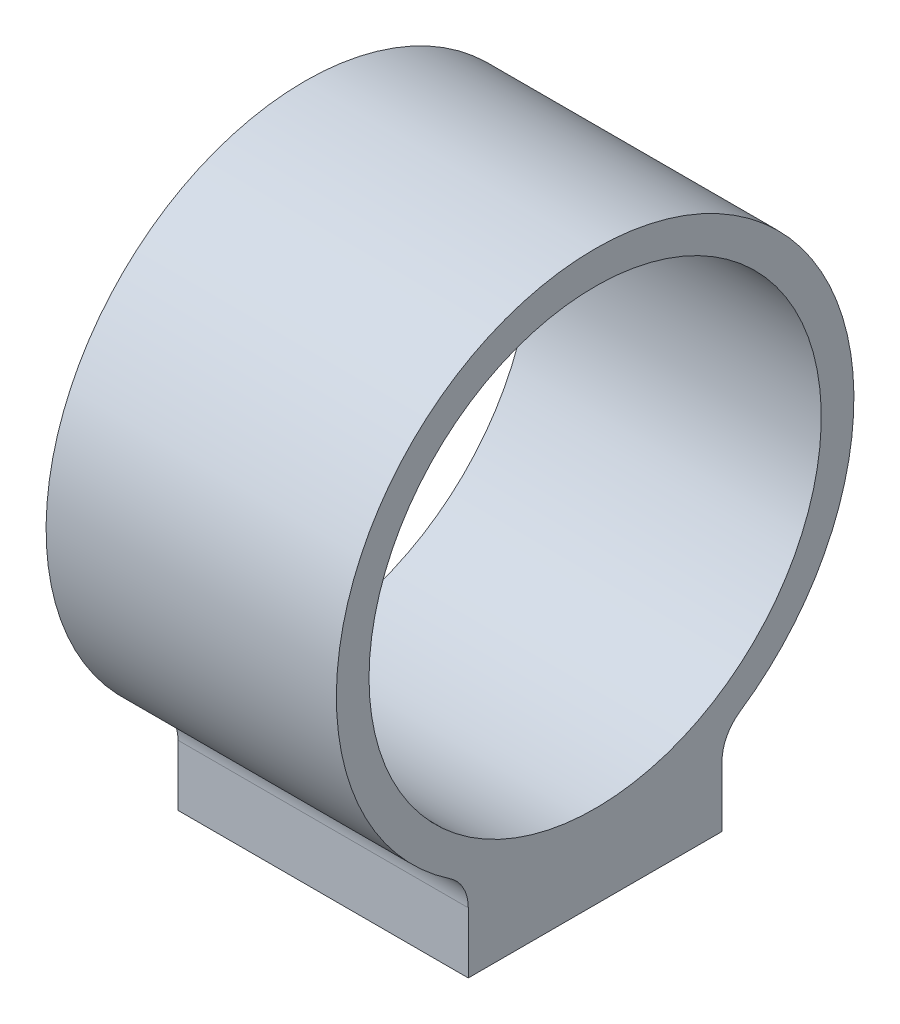
SolidWorks part; units mm, degrees
ref_plane "Front Plane" through (0, 0, 0) normal (0, 0, 1) x (1, 0, 0)
ref_plane "Top Plane" through (0, 0, 0) normal (0, 1, 0) x (1, 0, 0)
ref_plane "Right Plane" through (0, 0, 0) normal (1, 0, 0) x (0, 0, -1)
sketch "Sketch1" plane through (0, 0, 0) normal (0, 1, 0) x (1, 0, 0)
  line L1 (0, 0) -> (17.78, 0)
  line L2 (0, 0) -> (0, 15.54)
  line L3 (0, 15.54) -> (17.78, 15.54)
  line L4 (17.78, 0) -> (17.78, 15.54)
  dimension "D1" = 17.78
  dimension "D2" = 15.54
extrude "Boss-Extrude1" add sketch "Sketch1" along normal blind 3.1
sketch "Sketch3" plane through (0, 0, 0) normal (-1, 0, 0) x (0, 0, 1)
  line L1 (-15.54, 3.1) -> (0, 3.1) construction
  line L3 (-15.54, 3.1) -> (-15.54, 5.1352)
  line L4 (0, 3.1) -> (0, 5.1352)
  line L5 (-15.54, 3.1) -> (0, 3.1)
  circle A0 centre (-7.77, 18.95) radius 13.85
  arc A1 (0, 5.1352) -> (-15.54, 5.1352) centre (-7.77, 18.95) ccw
  dimension "D1" = 27.7
  dimension "D2" = 2
extrude "Boss-Extrude2" add sketch "Sketch3" against normal up to surface (17.78 mm away) up to face at (17.78, 1.55, -7.77)
fillet "Fillet1" radius 2.54 2 edges at (8.89, 5.1352, 0) (8.89, 5.1352, -15.54)
